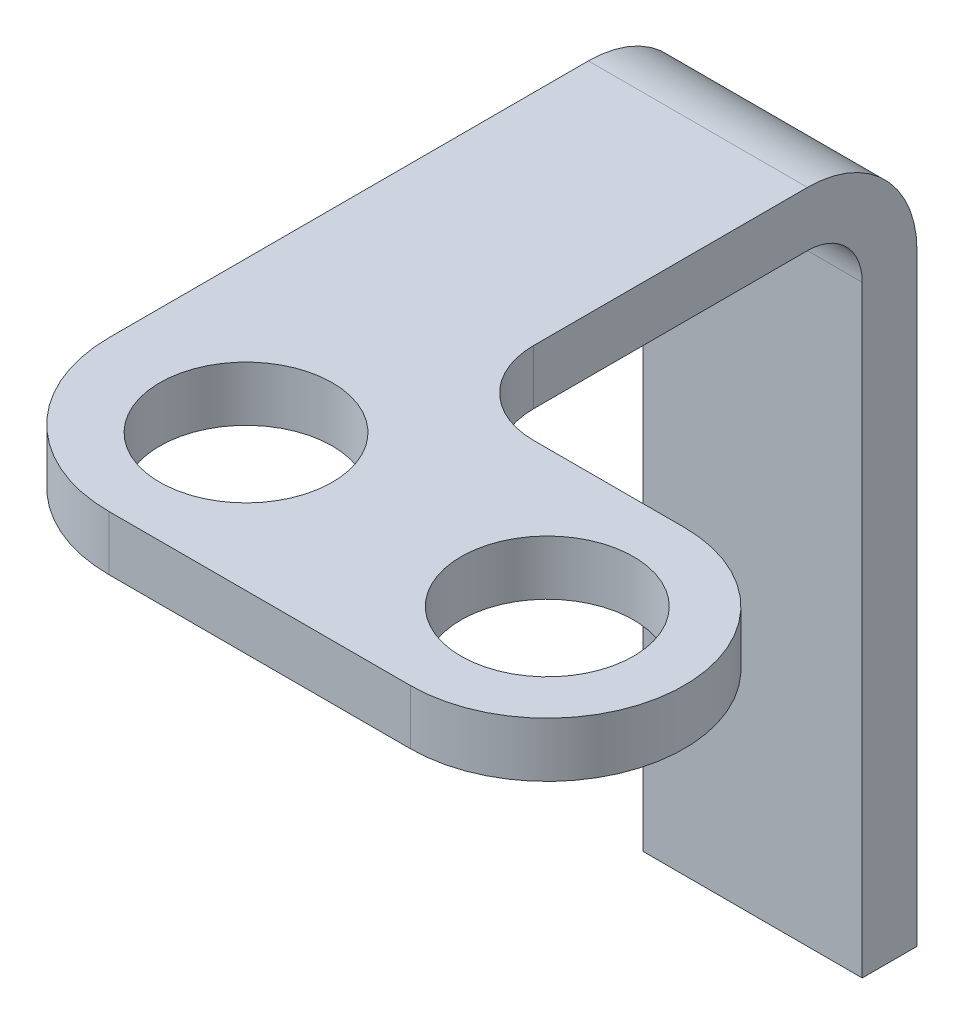
SolidWorks part; units mm, degrees
material "Copper"
ref_plane "Front Plane" through (0, 0, 0) normal (0, 0, 1) x (1, 0, 0)
ref_plane "Top Plane" through (0, 0, 0) normal (0, 1, 0) x (1, 0, 0)
ref_plane "Right Plane" through (0, 0, 0) normal (1, 0, 0) x (0, 0, -1)
sketch "Sketch1" plane through (0, 0, 0) normal (1, 0, 0) x (0, 0, -1)
  line L0 (0, -25) -> (0, -3)
  line L1 (-3, 0) -> (-21, 0)
  arc A0 (0, -3) -> (-3, 0) centre (-3, -3) ccw
  point P6 (0, 0)
  dimension "D1" = 3
  dimension "D2" = 25
  dimension "D4" = 18
extrude "Extrude-Thin1" add sketch "Sketch1" along normal blind 8 thin thin type mid plane wall 2
chamfer "Chamfer1" distance 6 angle 45 1 edges at (0, 0, 21)
sketch "Sketch2" plane through (0, 1, 0) normal (0, 1, 0) x (1, 0, 0)
  line L0 (7.9172, -21) -> (16.5, -21) construction
  line L1 (0, -20.5) -> (0, -3)
  line L2 (11, -16) -> (16.5, -16)
  line L3 (5.5, -26) -> (16.5, -26)
  line L5 (8, -21) -> (6, -21) construction
  line L6 (8, -3) -> (8, -21) construction
  line L11 (8, -13) -> (0, -3)
  circle A1 centre (16.5, -21) radius 3.15
  circle A2 centre (5.5, -21) radius 3.15
  arc A3 (16.5, -26) -> (16.5, -16) centre (16.5, -21) ccw
  arc A4 (5.5, -26) -> (0, -20.5) centre (5.5, -20.5) cw
  arc A6 (11, -16) -> (8, -13) centre (11, -13) cw
  point P4 (5.5, -21)
  point P13 (8, -83.1034)
  dimension "D1" = 6.3
  dimension "D2" = 5
  dimension "D3" = 3
  dimension "D4" = 2.5
  dimension "D5" = 11
extrude "Boss-Extrude1" add sketch "Sketch2" against normal blind 2
sketch "Sketch3" plane through (0, 1, 0) normal (0, 1, 0) x (1, 0, 0)
  circle A0 centre (5.5, -21) radius 3.15
  arc A1 (3.5367, -18.5367) -> (8, -19.0836) centre (5.5, -21) ccw construction
extrude "Cut-Extrude1" cut sketch "Sketch3" against normal blind 10.6
